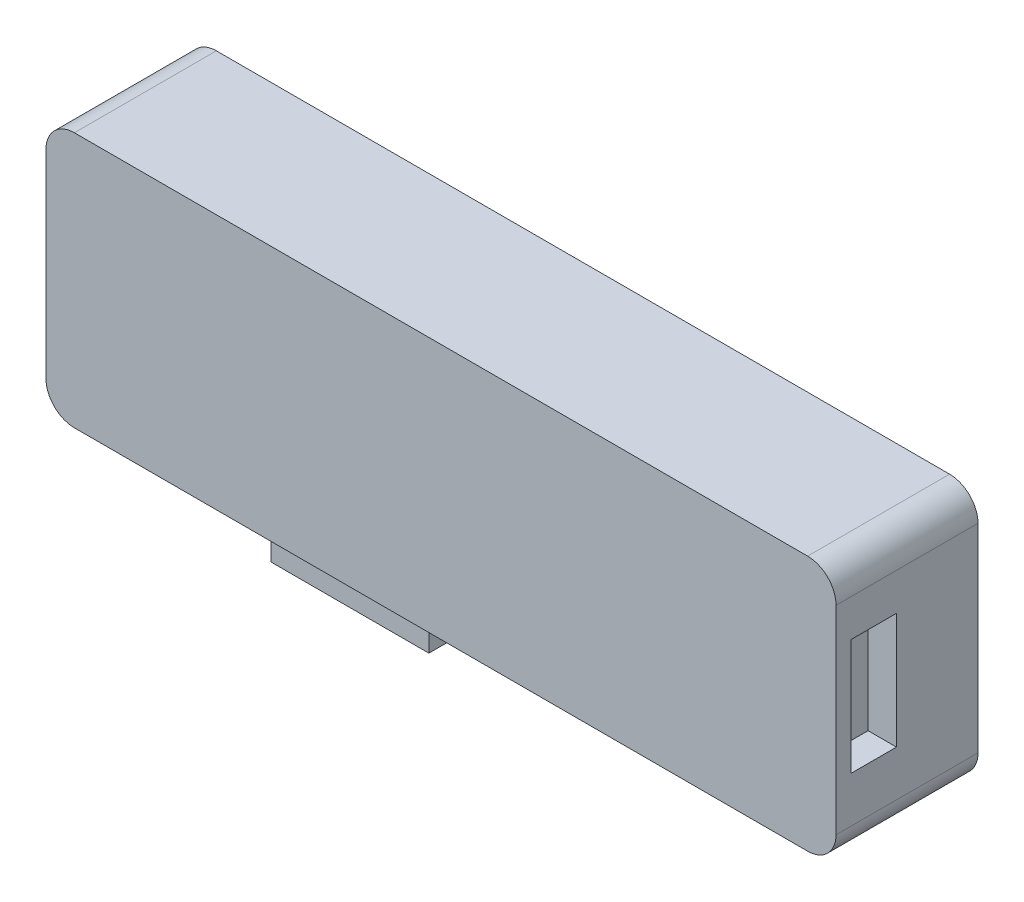
SolidWorks part; units mm, degrees
ref_plane "Front Plane" through (0, 0, 0) normal (0, 0, 1) x (1, 0, 0)
ref_plane "Top Plane" through (0, 0, 0) normal (0, 1, 0) x (1, 0, 0)
ref_plane "Right Plane" through (0, 0, 0) normal (1, 0, 0) x (0, 0, -1)
sketch "Sketch1" plane through (0, 0, 0) normal (0, 0, 1) x (1, 0, 0)
  line L0 (-19.05, 11.43) -> (46.5422, 11.43)
  line L1 (20.32, -10.16) -> (-20.32, -10.16) construction
  line L2 (20.32, -10.16) -> (20.32, 10.16) construction
  line L3 (20.32, 10.16) -> (-20.32, 10.16) construction
  line L4 (-20.32, -10.16) -> (-20.32, 10.16) construction
  line L5 (20.32, -10.16) -> (-20.32, 10.16) construction
  line L6 (20.32, 10.16) -> (-20.32, -10.16) construction
  line L7 (47.8122, 6.5945) -> (13.462, 6.5945) construction
  line L8 (47.8122, 6.5945) -> (47.8122, -6.5945) construction
  line L9 (47.8122, -6.5945) -> (13.462, -6.5945) construction
  line L10 (13.462, 6.5945) -> (13.462, -6.5945) construction
  line L11 (-20.32, -10.16) -> (47.8122, -10.16) construction
  line L12 (-20.32, -10.16) -> (-20.32, 10.16) construction
  line L13 (-20.32, 10.16) -> (47.8122, 10.16) construction
  line L14 (47.8122, -10.16) -> (47.8122, 10.16) construction
  line L15 (49.0822, -8.89) -> (49.0822, 8.89)
  line L16 (-19.05, -11.43) -> (46.5422, -11.43)
  line L17 (-21.59, -8.89) -> (-21.59, 8.89)
  line L18 (-21.59, -11.43) -> (-21.59, 11.43) construction
  line L19 (-21.59, 11.43) -> (49.0822, 11.43) construction
  line L20 (-21.59, -11.43) -> (49.0822, -11.43) construction
  line L21 (49.0822, -11.43) -> (49.0822, 11.43) construction
  arc A0 (-21.59, 8.89) -> (-19.05, 11.43) centre (-19.05, 8.89) cw
  arc A1 (-19.05, -11.43) -> (-21.59, -8.89) centre (-19.05, -8.89) cw
  arc A2 (46.5422, -11.43) -> (49.0822, -8.89) centre (46.5422, -8.89) ccw
  arc A3 (46.5422, 11.43) -> (49.0822, 8.89) centre (46.5422, 8.89) cw
  point P0 (0, 0)
  dimension "D2" = 2.54
  dimension "D3" = 2.54
  dimension "D4" = 2.54
  dimension "D5" = 2.54
  dimension "D1" = 1.27
extrude "Boss-Extrude1" add sketch "Sketch1" against normal blind 12.7 contours A2 L15 A3 L0 A0 L17 A1 L16
sketch "Sketch2" plane through (49.0822, 0, 0) normal (1, 0, 0) x (0, 0, -1)
  line L0 (1.8501, 0.3831) -> (4.8754, 0.3831) construction
  line L1 (1.8501, 0.6303) -> (1.8501, 0.1358) construction
  line L2 (4.8754, 4.611) -> (4.8754, -2.4701) construction
  line L4 (1.3174, -4.7992) -> (5.408, -4.7992)
  line L5 (1.3174, -4.7992) -> (1.3174, 5.5653)
  line L6 (1.3174, 5.5653) -> (5.408, 5.5653)
  line L7 (5.408, -4.7992) -> (5.408, 5.5653)
  line L8 (1.3174, -4.7992) -> (5.408, 5.5653) construction
  line L9 (1.3174, 5.5653) -> (5.408, -4.7992) construction
  point P6 (3.3627, 0.3831)
extrude "Cut-Extrude1" cut sketch "Sketch2" against normal blind 2.54
sketch "Sketch3" plane through (0, -11.43, 0) normal (0, -1, 0) x (1, 0, 0)
  line L0 (9.864, -9.334) -> (-4.276, -9.334)
  line L1 (8.594, -4.064) -> (-3.006, -4.064) construction
  line L2 (8.594, -4.064) -> (8.594, -8.064) construction
  line L3 (8.594, -8.064) -> (-3.006, -8.064) construction
  line L4 (-3.006, -4.064) -> (-3.006, -8.064) construction
  line L5 (8.594, -4.064) -> (-3.006, -8.064) construction
  line L6 (8.594, -8.064) -> (-3.006, -4.064) construction
  line L7 (-4.276, -2.794) -> (-4.276, -9.334)
  line L8 (9.864, -2.794) -> (-4.276, -2.794)
  line L9 (9.864, -2.794) -> (9.864, -9.334)
  line L10 (5.298, -4.81) -> (5.298, -7.318)
  line L11 (5.044, -5.064) -> (0.544, -5.064) construction
  line L12 (5.044, -5.064) -> (5.044, -7.064) construction
  line L13 (5.044, -7.064) -> (0.544, -7.064) construction
  line L14 (0.544, -5.064) -> (0.544, -7.064) construction
  line L15 (5.044, -5.064) -> (0.544, -7.064) construction
  line L16 (5.044, -7.064) -> (0.544, -5.064) construction
  line L17 (5.298, -7.318) -> (0.29, -7.318)
  line L18 (0.29, -4.81) -> (0.29, -7.318)
  line L19 (5.298, -4.81) -> (0.29, -4.81)
  point P0 (2.794, -6.064)
  point P11 (2.794, -6.064)
  dimension "D1" = 1.27
  dimension "D2" = 0.254
extrude "Boss-Extrude2" add sketch "Sketch3" along normal offset from surface (4.3946 mm away) 1.016
